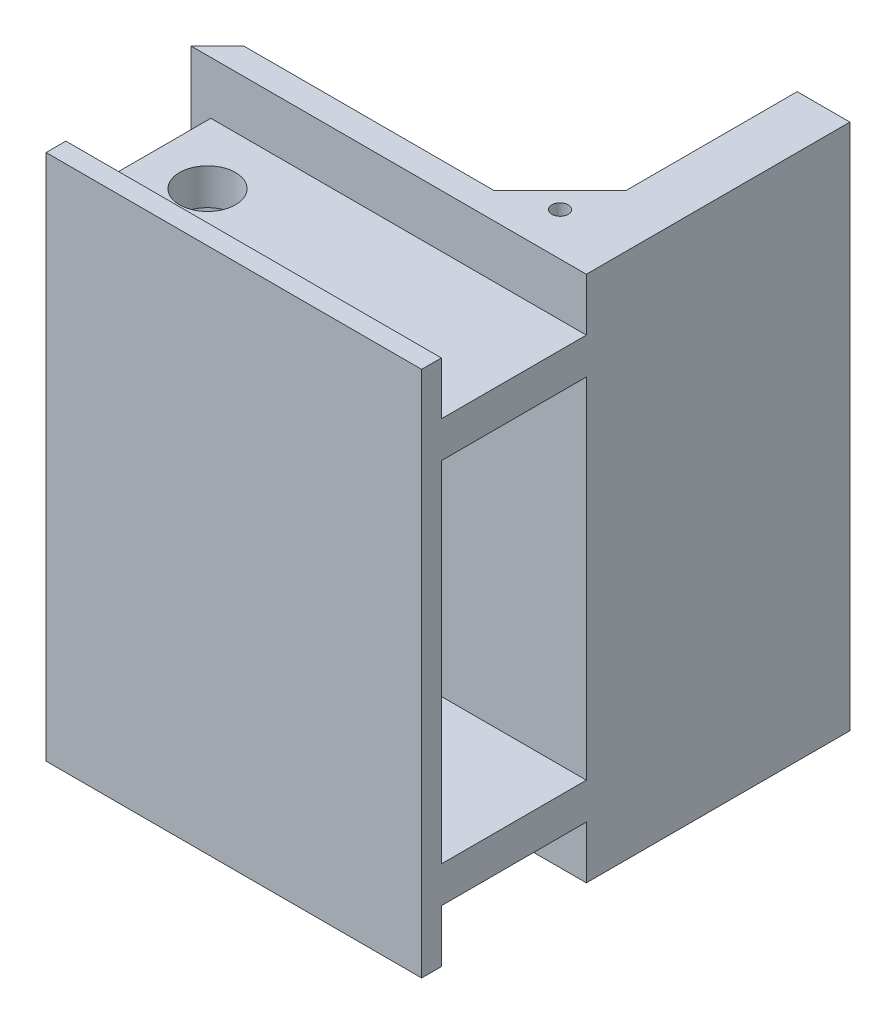
SolidWorks part; units mm, degrees
ref_plane "Front Plane" through (0, 0, 0) normal (0, 0, 1) x (1, 0, 0)
ref_plane "Top Plane" through (0, 0, 0) normal (0, 1, 0) x (1, 0, 0)
ref_plane "Right Plane" through (0, 0, 0) normal (1, 0, 0) x (0, 0, -1)
sketch "Sketch1" plane through (0, 0, 0) normal (0, 1, 0) x (1, 0, 0)
  line L0 (-17.3516, 20.3127) -> (-57.3516, -19.6873)
  line L1 (-17.3516, 20.3127) -> (2.6484, 20.3127)
  line L2 (-17.3516, 20.3127) -> (-17.3516, -19.6873)
  line L3 (-17.3516, -19.6873) -> (2.6484, -19.6873)
  line L4 (2.6484, 20.3127) -> (2.6484, -19.6873)
  line L5 (-57.3516, -19.6873) -> (-17.3516, -19.6873)
  dimension "D1" = 20
  dimension "D2" = 40
  dimension "D3" = 40
extrude "Boss-Extrude1" add sketch "Sketch1" against normal blind 80 contours L0 L5 L2 | L4 L1 L2 L3
sketch "Sketch8" plane through (2.6484, 0, 0) normal (1, 0, 0) x (0, 0, -1)
  line L0 (-19.6873, -80) -> (-19.6873, 0) construction
  line L14 (-19.6873, -8) -> (-44.6873, -8)
  line L15 (-19.6873, -8) -> (-19.6873, -72)
  line L16 (-19.6873, -72) -> (-44.6873, -72)
  line L17 (-44.6873, -8) -> (-44.6873, -72)
  dimension "D2" = 64
  dimension "D3" = 8
  dimension "D12" = 25
extrude "Boss-Extrude2" add sketch "Sketch8" against normal blind 57
sketch "Sketch12" plane through (0, -72, 0) normal (0, -1, 0) x (1, 0, 0)
  line L0 (2.6484, 44.6873) -> (2.6484, 19.6873) construction
  line L1 (-54.3516, 44.6873) -> (2.6484, 44.6873)
  line L2 (-54.3516, 44.6873) -> (-54.3516, 38.6873)
  line L3 (-54.3516, 38.6873) -> (2.6484, 38.6873)
  line L4 (2.6484, 44.6873) -> (2.6484, 38.6873)
  dimension "D1" = 6
extrude "Boss-Extrude3" add sketch "Sketch12" along normal blind 8
sketch "Sketch14" plane through (0, -8, 0) normal (0, 1, 0) x (1, 0, 0)
  line L0 (2.6484, -19.6873) -> (2.6484, -44.6873) construction
  line L1 (-54.3516, -44.6873) -> (2.6484, -44.6873)
  line L2 (-54.3516, -44.6873) -> (-54.3516, -38.6873)
  line L3 (-54.3516, -38.6873) -> (2.6484, -38.6873)
  line L4 (2.6484, -44.6873) -> (2.6484, -38.6873)
  dimension "D1" = 6
extrude "Boss-Extrude4" add sketch "Sketch14" along normal blind 8
sketch "Sketch17" plane through (0, 0, -20.3127) normal (0, 0, -1) x (-1, 0, 0)
  line L1 (5.3516, 0) -> (53.3516, 0)
  line L2 (5.3516, 0) -> (5.3516, -80)
  line L3 (5.3516, -80) -> (53.3516, -80)
  line L4 (53.3516, 0) -> (53.3516, -80)
  line L6 (57.3516, -80) -> (57.3516, 0) construction
  line L7 (-2.6484, -80) -> (-2.6484, 0) construction
  line L8 (17.3516, 0) -> (57.3516, 0) construction
  line L9 (17.3516, -80) -> (57.3516, -80) construction
  dimension "D3" = 4
  dimension "D4" = 8
extrude "Cut-Extrude4" cut sketch "Sketch17" against normal blind 36
chamfer "Chamfer1" distance 10 angle 45 1 edges at (-5.3516, -40, 15.6873)
sketch "Sketch16" plane through (0, 0, 15.6873) normal (0, 0, -1) x (-1, 0, 0)
  line L0 (53.3516, -80) -> (53.3516, 0) construction
  line L1 (53.3516, -76) -> (5.3516, -76)
  line L2 (53.3516, -76) -> (53.3516, -4)
  line L3 (53.3516, -4) -> (5.3516, -4)
  line L4 (5.3516, -76) -> (5.3516, -4)
  line L5 (5.3516, 0) -> (5.3516, -80) construction
  line L6 (53.3516, 0) -> (15.3516, 0) construction
  line L7 (15.3516, -80) -> (53.3516, -80) construction
  dimension "D1" = 4
  dimension "D2" = 4
extrude "Cut-Extrude5" cut sketch "Sketch16" along normal blind 10
sketch "Sketch19" plane through (0, 0, 0) normal (0, 1, 0) x (1, 0, 0)
  line L0 (-15.3516, -15.6873) -> (2.6484, -15.6873) construction
  line L1 (-5.3516, -5.6873) -> (-15.3516, -15.6873) construction
  line L2 (2.6484, 20.3127) -> (2.6484, -19.6873) construction
  line L3 (-5.3516, -5.6873) -> (-5.3516, -19.6873) construction
  line L4 (-57.3516, -19.6873) -> (2.6484, -19.6873) construction
  line L5 (-10.3516, -10.6873) -> (-5.3516, -15.6873) construction
  circle A0 centre (-7.8516, -13.1873) radius 1.25
  dimension "D1" = 2.5
extrude "Cut-Extrude6" cut sketch "Sketch19" against normal through all
sketch "Sketch21" plane through (-54.3516, 0, 0) normal (-1, 0, 0) x (0, 0, 1)
  line L0 (19.6873, -40) -> (38.6873, -40) construction
  line L1 (19.6873, -13.5) -> (38.6873, -13.5)
  line L2 (19.6873, -13.5) -> (19.6873, -66.5)
  line L3 (19.6873, -66.5) -> (38.6873, -66.5)
  line L4 (38.6873, -13.5) -> (38.6873, -66.5)
  line L8 (44.6873, -40) -> (19.6873, -40) construction
  line L9 (44.6873, 0) -> (44.6873, -80) construction
  line L10 (19.6873, -80) -> (19.6873, 0) construction
  dimension "D1" = 19
  dimension "D2" = 53
extrude "Cut-Extrude7" cut sketch "Sketch21" against normal through all
sketch "Sketch22" plane through (0, -72, 0) normal (0, -1, 0) x (1, 0, 0)
  line L0 (-54.3516, 29.1873) -> (2.6484, 29.1873) construction
  line L1 (-54.3516, 38.6873) -> (-54.3516, 19.6873) construction
  line L2 (2.6484, 38.6873) -> (2.6484, 19.6873) construction
  line L3 (-54.3516, 19.6873) -> (2.6484, 19.6873) construction
  line L4 (-45.3516, 22.1873) -> (-54.3516, 22.1873)
  line L6 (2.6484, 44.6873) -> (-54.3516, 44.6873) construction
  line L7 (-54.3516, 38.6873) -> (2.6484, 38.6873) construction
  circle A0 centre (-45.3516, 29.1873) radius 4.25
  circle A2 centre (-45.3516, 29.1873) radius 7
  dimension "D1" = 8.5
  dimension "D2" = 14
  dimension "D3" = 9
extrude "Cut-Extrude8" cut sketch "Sketch22" against normal through all contours A0
sketch "Sketch25" plane through (-54.3516, 0, 0) normal (-1, 0, 0) x (0, 0, 1)
  line L0 (44.6873, -80) -> (38.6873, -80) construction
  line L1 (38.6873, -72) -> (41.6873, -72)
  line L2 (38.6873, -72) -> (38.6873, -80)
  line L3 (38.6873, -80) -> (41.6873, -80)
  line L4 (41.6873, -72) -> (41.6873, -80)
  line L5 (38.6873, 0) -> (44.6873, 0) construction
  line L6 (38.6873, -66.5) -> (41.6873, -66.5)
  line L7 (38.6873, -66.5) -> (38.6873, -13.5)
  line L8 (38.6873, -13.5) -> (41.6873, -13.5)
  line L9 (41.6873, -66.5) -> (41.6873, -13.5)
  line L10 (38.6873, -8) -> (41.6873, -8)
  line L11 (38.6873, -8) -> (38.6873, 0)
  line L12 (38.6873, 0) -> (41.6873, 0)
  line L13 (41.6873, -8) -> (41.6873, 0)
  line L14 (38.6873, -13.5) -> (19.6873, -13.5) construction
  dimension "D1" = 3
extrude "Cut-Extrude11" cut sketch "Sketch25" against normal through all
